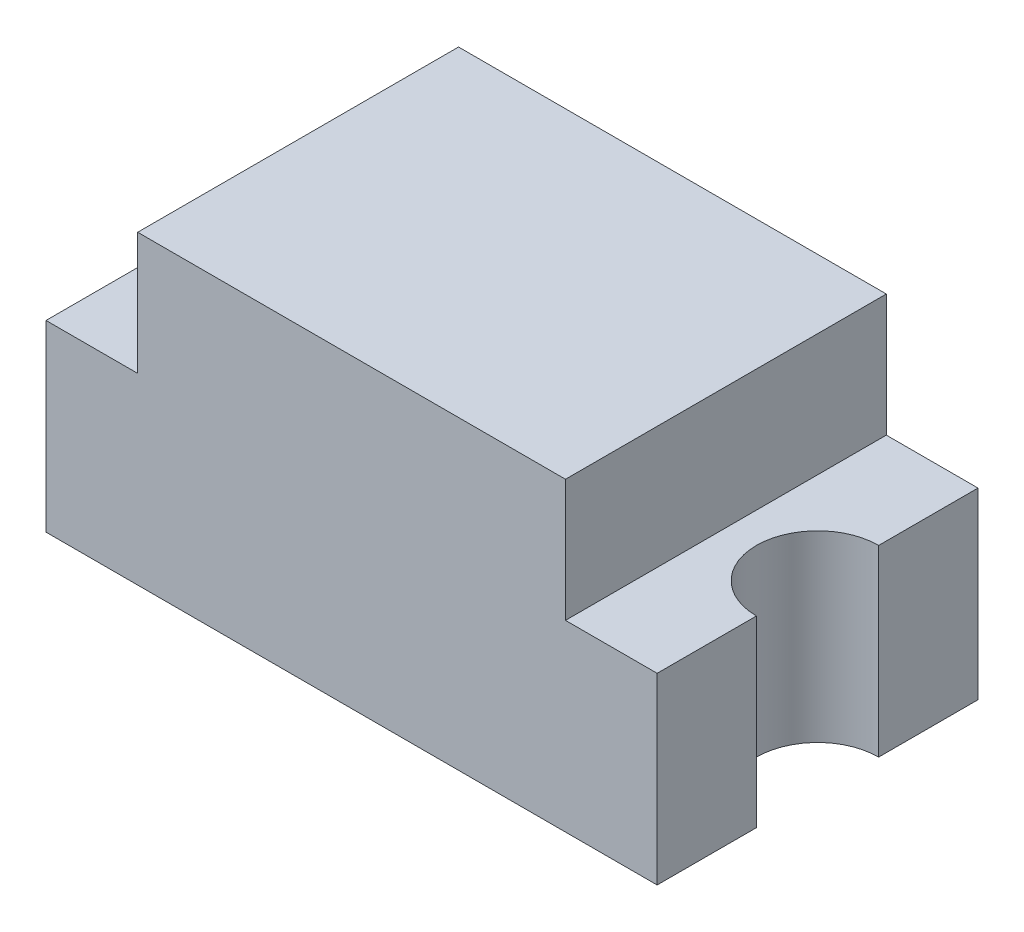
SolidWorks part; units mm, degrees
ref_plane "Front Plane" through (0, 0, 0) normal (0, 0, 1) x (1, 0, 0)
ref_plane "Top Plane" through (0, 0, 0) normal (0, 1, 0) x (1, 0, 0)
ref_plane "Right Plane" through (0, 0, 0) normal (1, 0, 0) x (0, 0, -1)
sketch "Sketch1" plane through (0, 0, 0) normal (0, 1, 0) x (1, 0, 0)
  line L1 (-1, -0.525) -> (1, -0.525)
  line L2 (-1, -0.525) -> (-1, 0.525)
  line L3 (-1, 0.525) -> (1, 0.525)
  line L4 (1, -0.525) -> (1, 0.525)
  line L5 (-1, -0.525) -> (1, 0.525) construction
  line L6 (-1, 0.525) -> (1, -0.525) construction
  circle A0 centre (1, 0) radius 0.2
  circle A1 centre (-1, 0) radius 0.2
  point P0 (0, 0)
  dimension "D3" = 0.4
  dimension "D1" = 2
  dimension "D2" = 1.05
extrude "Boss-Extrude1" add sketch "Sketch1" along normal blind 0.6 contours A1 L2 L1 L4 A0 L3
sketch "Sketch4" plane through (0, 0.6, 0) normal (0, 1, 0) x (1, 0, 0)
  line L0 (-1, 0.525) -> (1, 0.525) construction
  line L1 (-0.7, -0.525) -> (0.7, -0.525)
  line L2 (-0.7, -0.525) -> (-0.7, 0.525)
  line L3 (-0.7, 0.525) -> (0.7, 0.525)
  line L4 (0.7, -0.525) -> (0.7, 0.525)
  line L5 (-0.7, -0.525) -> (0.7, 0.525) construction
  line L6 (-0.7, 0.525) -> (0.7, -0.525) construction
  point P0 (0, 0)
  dimension "D1" = 1.4
extrude "Boss-Extrude3" add sketch "Sketch4" along normal blind 0.4
